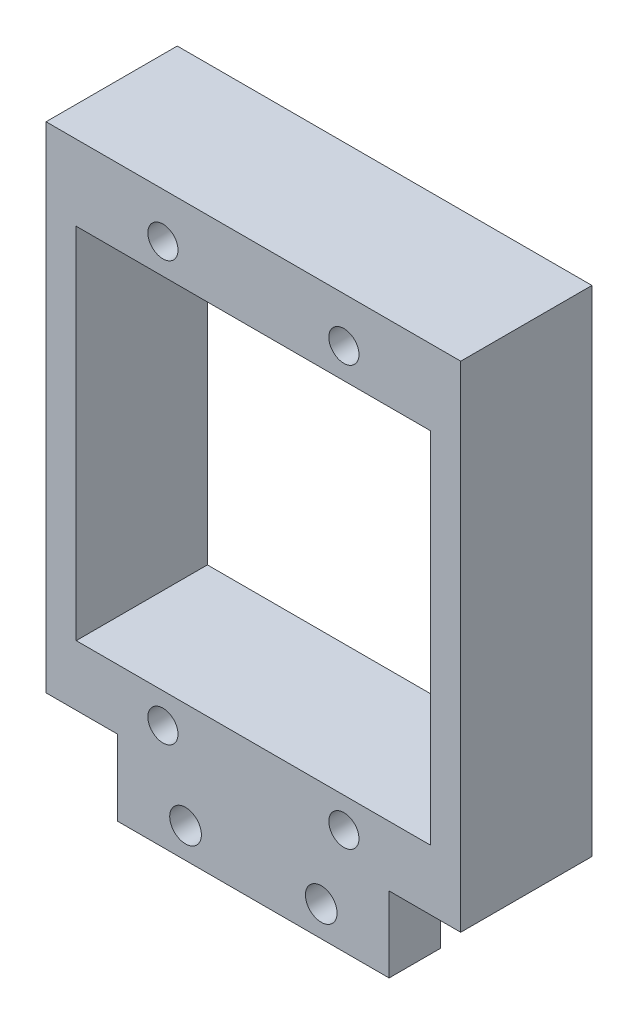
SolidWorks part; units mm, degrees
ref_plane "Front Plane" through (0, 0, 0) normal (0, 0, 1) x (1, 0, 0)
ref_plane "Top Plane" through (0, 0, 0) normal (0, 1, 0) x (1, 0, 0)
ref_plane "Right Plane" through (0, 0, 0) normal (1, 0, 0) x (0, 0, -1)
sketch "Sketch1" plane through (0, 0, 0) normal (0, 0, 1) x (1, 0, 0)
  line L0 (0, 0) -> (0, 21.5273) construction
  line L2 (-9, -2.5) -> (9, -2.5)
  line L3 (-9, -2.5) -> (-9, 2.5)
  line L4 (-9, 2.5) -> (9, 2.5)
  line L5 (9, -2.5) -> (9, 2.5)
  line L6 (-9, -2.5) -> (9, 2.5) construction
  line L7 (-9, 2.5) -> (9, -2.5) construction
  dimension "D1" = 18
  dimension "D2" = 5
extrude "Boss-Extrude1" add sketch "Sketch1" along normal blind 3.4
sketch "Sketch2" plane through (0, 0, 3.4) normal (0, 0, 1) x (1, 0, 0)
  line L0 (0, 0) -> (0, 7.329) construction
  line L1 (9, 2.5) -> (-9, 2.5) construction
  line L2 (-13.75, 6.5) -> (13.75, 6.5)
  line L3 (-13.75, 6.5) -> (-13.75, 2.5)
  line L4 (-13.75, 2.5) -> (13.75, 2.5)
  line L5 (13.75, 6.5) -> (13.75, 2.5)
  line L6 (-13.75, 6.5) -> (13.75, 2.5) construction
  line L7 (-13.75, 2.5) -> (13.75, 6.5) construction
  point P3 (0, 4.5)
  dimension "D1" = 4
  dimension "D2" = 27.5
extrude "Boss-Extrude2" add sketch "Sketch2" against normal blind 8.7
sketch "Sketch3" plane through (0, 6.5, 0) normal (0, 1, 0) x (1, 0, 0)
  line L0 (-11.75, -3.4) -> (11.75, -3.4) construction
  line L1 (-13.75, 5.3) -> (-11.75, 5.3)
  line L2 (-13.75, 5.3) -> (-13.75, -3.4)
  line L3 (-13.75, -3.4) -> (-11.75, -3.4)
  line L4 (-11.75, 5.3) -> (-11.75, -3.4)
  line L5 (13.75, 5.3) -> (11.75, 5.3)
  line L6 (13.75, 5.3) -> (13.75, -3.4)
  line L7 (13.75, -3.4) -> (11.75, -3.4)
  line L8 (11.75, 5.3) -> (11.75, -3.4)
  line L9 (13.75, -3.4) -> (-13.75, -3.4) construction
  dimension "D1" = 2
  dimension "D2" = 2
extrude "Boss-Extrude3" add sketch "Sketch3" along normal blind 23.8
sketch "Sketch4" plane through (0, 30.3, 0) normal (0, 1, 0) x (1, 0, 0)
  line L1 (-13.75, 5.3) -> (13.75, 5.3)
  line L2 (-13.75, 5.3) -> (-13.75, -3.4)
  line L3 (-13.75, -3.4) -> (13.75, -3.4)
  line L4 (13.75, 5.3) -> (13.75, -3.4)
extrude "Boss-Extrude4" add sketch "Sketch4" along normal blind 5
sketch "Sketch5" plane through (0, 0, 3.4) normal (0, 0, 1) x (1, 0, 0)
  line L0 (-9, -0.5) -> (9, -0.5) construction
  line L1 (-9, 2.5) -> (-9, -2.5) construction
  line L2 (9, -2.5) -> (9, 2.5) construction
  line L3 (0, -0.5) -> (0, 11.0457) construction
  line L4 (0, 11.0457) -> (-4.5, -0.5) construction
  line L5 (0, 11.0457) -> (4.5, -0.5) construction
  line L6 (-9, -2.5) -> (9, -2.5) construction
  line L7 (-13.75, 4.5) -> (13.75, 4.5) construction
  line L8 (-13.75, 35.3) -> (-13.75, 2.5) construction
  line L9 (13.75, 2.5) -> (13.75, 35.3) construction
  line L10 (-6, 4.5) -> (0, 11.0457) construction
  line L11 (0, 11.0457) -> (6, 4.5) construction
  line L12 (11.75, 6.5) -> (-11.75, 6.5) construction
  line L13 (-13.75, 32.3) -> (13.75, 32.3) construction
  line L14 (0, 32.3) -> (0, 4.5) construction
  line L15 (0, 18.4) -> (13.75, 18.4) construction
  line L16 (-11.75, 30.3) -> (11.75, 30.3) construction
  circle A0 centre (-4.5, -0.5) radius 1.05
  circle A1 centre (4.5, -0.5) radius 1.05
  circle A2 centre (-6, 4.5) radius 1
  circle A3 centre (6, 4.5) radius 1
  circle A4 centre (6, 32.3) radius 1
  circle A5 centre (-6, 32.3) radius 1
  dimension "D1" = 2.1
  dimension "D4" = 2
  dimension "D2" = 9
  dimension "D3" = 2
  dimension "D5" = 12
  dimension "D6" = 2
  dimension "D7" = 2
extrude "Cut-Extrude1" cut sketch "Sketch5" against normal through all
